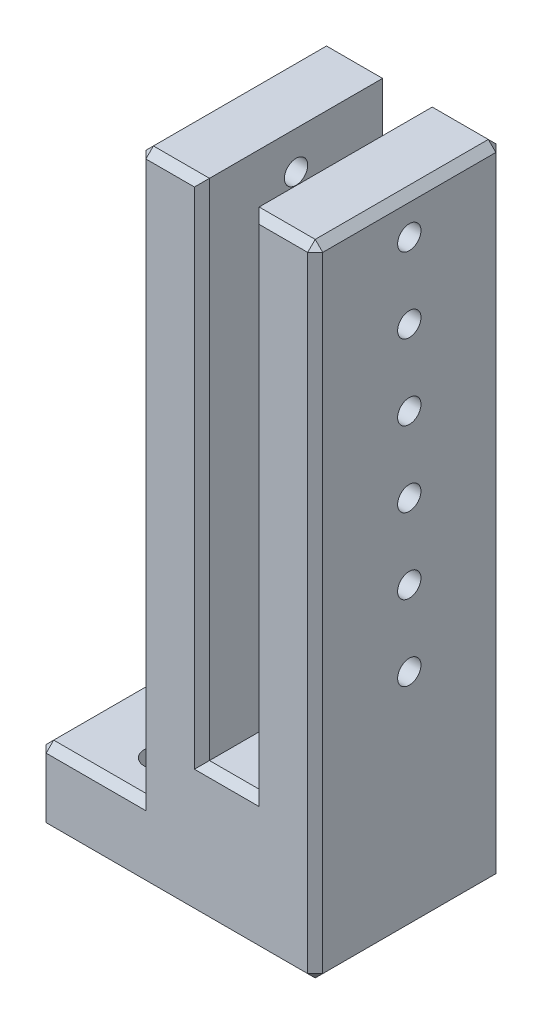
SolidWorks part; units mm, degrees
material "PBT General Purpose"
ref_plane "Front Plane" through (0, 0, 0) normal (0, 0, 1) x (1, 0, 0)
ref_plane "Top Plane" through (0, 0, 0) normal (0, 1, 0) x (1, 0, 0)
ref_plane "Right Plane" through (0, 0, 0) normal (1, 0, 0) x (0, 0, -1)
sketch "Sketch1" plane through (0, 0, 0) normal (0, 1, 0) x (1, 0, 0)
  line L1 (0, 0) -> (50, 0)
  line L2 (0, 0) -> (0, 25)
  line L3 (0, 25) -> (50, 25)
  line L4 (50, 0) -> (50, 25)
  dimension "D1" = 50
  dimension "D2" = 25
extrude "Boss-Extrude1" add sketch "Sketch1" along normal blind 10
sketch "Sketch2" plane through (0, 10, 0) normal (0, 1, 0) x (1, 0, 0)
  line L0 (50, 25) -> (0, 25) construction
  line L1 (15, 25) -> (35, 25)
  line L2 (15, 25) -> (15, 0)
  line L3 (15, 0) -> (35, 0)
  line L4 (35, 25) -> (35, 0)
  line L5 (0, 0) -> (50, 0) construction
  point P8 (25, 25)
  point P9 (25, 25)
  dimension "D1" = 20
extrude "Boss-Extrude2" add sketch "Sketch2" along normal blind 75
sketch "Sketch3" plane through (0, 85, 0) normal (0, 1, 0) x (1, 0, 0)
  line L0 (35, 25) -> (15, 25) construction
  line L1 (21.7, 25) -> (28.3, 25)
  line L2 (21.7, 25) -> (21.7, 0)
  line L3 (21.7, 0) -> (28.3, 0)
  line L4 (28.3, 25) -> (28.3, 0)
  line L5 (15, 0) -> (35, 0) construction
  point P8 (25, 25)
  point P9 (25, 25)
  dimension "D1" = 6.6
extrude "Cut-Extrude1" cut sketch "Sketch3" against normal up to surface (75 mm away) up to face at (7.5, 10, -12.5)
sketch "Sketch4" plane through (15, 0, 0) normal (-1, 0, 0) x (0, 0, 1)
  line L0 (-12.5, 85) -> (-12.5, 80) construction
  line L1 (-25, 85) -> (0, 85) construction
  circle A0 centre (-12.5, 80) radius 1.55
  dimension "D1" = 5
  dimension "D2" = 3.1
extrude "Cut-Extrude2" cut sketch "Sketch4" against normal through all and the other way through all
pattern_linear "LPattern1" count 6 spacing 10 along (0, -1, 0) of "Cut-Extrude2"
sketch "Sketch5" plane through (0, 10, 0) normal (0, 1, 0) x (1, 0, 0)
  line L4 (35, 25) -> (35, 0)
  line L5 (35, 0) -> (50, 0)
  line L6 (50, 0) -> (50, 25)
  line L7 (50, 25) -> (35, 25)
  line L8 (35, 25) -> (35, 0)
  line L9 (35, 0) -> (50, 0)
  line L10 (50, 0) -> (50, 25)
  line L11 (50, 25) -> (35, 25)
  dimension "D1" = 0
extrude "Cut-Extrude3" cut sketch "Sketch5" against normal through all
ref_plane "Plane1" through (25, 0, 0) normal (1, 0, 0) x (0, 0, -1)
sketch "Sketch6" plane through (0, 0, 0) normal (0, -1, 0) x (1, 0, 0)
  line L0 (0, 0) -> (35, 0) construction
  line L1 (0, -25) -> (0, 0) construction
  circle A1 centre (10.0004, -5.9306) radius 1.9
  dimension "D1" = 5.9306
  dimension "D2" = 10.0004
  dimension "D3" = 3.8
extrude "Cut-Extrude4" cut sketch "Sketch6" against normal through all
ref_plane "Plane2" through (0, 0, -12.5) normal (0, 0, 1) x (1, 0, 0)
mirror "Mirror1" about plane through (0, 0, -12.5) normal (0, 0, 1) of "Cut-Extrude4"
sketch "Sketch7" plane through (0, 10, 0) normal (0, 1, 0) x (1, 0, 0)
  line L0 (0, 0) -> (35, 0) construction
  circle A1 centre (10.0004, 14.5906) radius 1.9
  circle A3 centre (10.0004, 5.9306) radius 1.9 construction
  circle A4 centre (10.0004, 5.9306) radius 1.9
  dimension "D1" = 14.5906
extrude "Cut-Extrude5" cut sketch "Sketch7" against normal through all
sketch "Sketch8" plane through (0, 0, 0) normal (0, 0, 1) x (1, 0, 0)
  line L0 (28.3, 10) -> (28.3, 85) construction
  line L1 (21.7, 10) -> (28.3, 10)
  line L2 (21.7, 10) -> (21.7, 18)
  line L3 (21.7, 18) -> (28.3, 18)
  line L4 (28.3, 10) -> (28.3, 18)
  dimension "D1" = 8
extrude "Boss-Extrude4" add sketch "Sketch8" against normal through all
sketch "Sketch11" plane through (35, 0, 0) normal (1, 0, 0) x (0, 0, -1)
  line L8 (0, 85) -> (0, 0)
  line L9 (0, 0) -> (25, 0)
  line L10 (25, 0) -> (25, 85)
  line L11 (25, 85) -> (0, 85)
  line L12 (0, 85) -> (0, 0)
  line L13 (0, 0) -> (25, 0)
  line L14 (25, 0) -> (25, 85)
  line L15 (25, 85) -> (0, 85)
  dimension "D1" = 0
extrude "Boss-Extrude5" add sketch "Sketch11" along normal blind 1.75
sketch "Sketch12" plane through (15, 0, 0) normal (-1, 0, 0) x (0, 0, 1)
  line L4 (-25, 10) -> (0, 10)
  line L5 (0, 10) -> (0, 85)
  line L6 (0, 85) -> (-25, 85)
  line L7 (-25, 85) -> (-25, 10)
  line L8 (-25, 10) -> (0, 10)
  line L9 (0, 10) -> (0, 85)
  line L10 (0, 85) -> (-25, 85)
  line L11 (-25, 85) -> (-25, 10)
  dimension "D1" = 0
extrude "Boss-Extrude6" add sketch "Sketch12" along normal blind 1.75
sketch "Sketch14" plane through (0, 10, 0) normal (0, 1, 0) x (1, 0, 0)
  line L0 (10.0004, 14.5906) -> (10.0004, 5.9306) construction
  circle A0 centre (10.0004, 10.2606) radius 1.9
  circle A1 centre (10.0004, 5.9306) radius 1.9 construction
extrude "Cut-Extrude7" cut sketch "Sketch14" against normal through all
sketch "Sketch15" plane through (28.3, 0, 0) normal (-1, 0, 0) x (0, 0, 1)
  circle A0 centre (-12.5, 30) radius 1.55 construction
  circle A1 centre (-12.5, 40) radius 1.55 construction
  circle A2 centre (-12.5, 50) radius 1.55 construction
  circle A3 centre (-12.5, 60) radius 1.55 construction
  circle A4 centre (-12.5, 70) radius 1.55 construction
  circle A5 centre (-12.5, 80) radius 1.55 construction
  circle A6 centre (-12.5, 30) radius 1.55
  circle A7 centre (-12.5, 40) radius 1.55
  circle A8 centre (-12.5, 50) radius 1.55
  circle A9 centre (-12.5, 60) radius 1.55
  circle A10 centre (-12.5, 70) radius 1.55
  circle A11 centre (-12.5, 80) radius 1.55
extrude "Cut-Extrude8" cut sketch "Sketch15" against normal through all and the other way through all
chamfer "Chamfer1" distance 1 angle 45 25 edges at (36.75, 0, -12.5) (36.75, 85, -12.5) (32.525, 85, 0) (36.75, 42.5, 0) (18.375, 0, 0) (0, 5, 0) (6.625, 10, 0) (13.25, 47.5, 0) (28.3, 51.5, 0) (25, 18, 0) (21.7, 51.5, 0) (17.475, 85, 0) (0, 5, -25) (0, 0, -12.5) (18.375, 0, -25) (36.75, 42.5, -25) (32.525, 85, -25) (28.3, 51.5, -25) (25, 18, -25) (21.7, 51.5, -25) (17.475, 85, -25) (13.25, 85, -12.5) (13.25, 47.5, -25) (6.625, 10, -25) (0, 10, -12.5)
